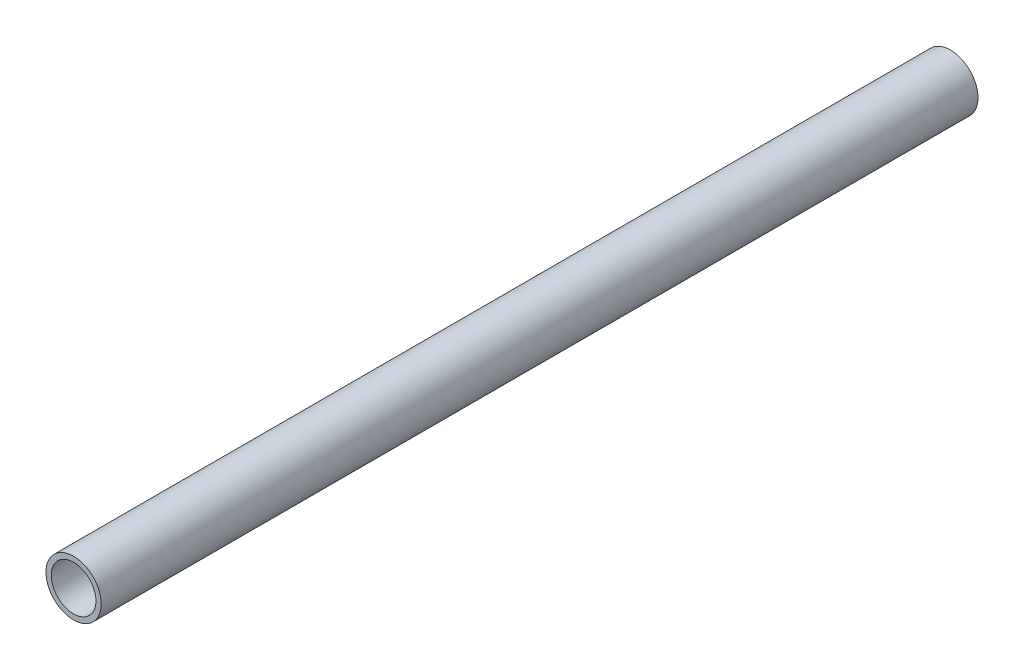
SolidWorks part; units mm, degrees
ref_plane "Front Plane" through (0, 0, 0) normal (0, 0, 1) x (1, 0, 0)
ref_plane "Top Plane" through (0, 0, 0) normal (0, 1, 0) x (1, 0, 0)
ref_plane "Right Plane" through (0, 0, 0) normal (1, 0, 0) x (0, 0, -1)
sketch "Sketch1" plane through (0, 0, 0) normal (0, 0, 1) x (1, 0, 0)
  circle A0 centre (0, 0) radius 6.477
  circle A1 centre (0, 0) radius 8.001
  dimension "D1" = 16.002
  dimension "D2" = 1.524
extrude "Boss-Extrude1" add sketch "Sketch1" against normal blind 254
equation "\"Pushrod_length\" = 10"
equation "\"Pushrod_outer_diameter\"= .63"
equation "\"Pushrod_thickness\" = .06"
equation "\"D1@Sketch1\"=\"Pushrod_outer_diameter\""
equation "\"D2@Sketch1\"=\"Pushrod_thickness\""
equation "\"D1@Boss-Extrude1\"=\"Pushrod_length\""
